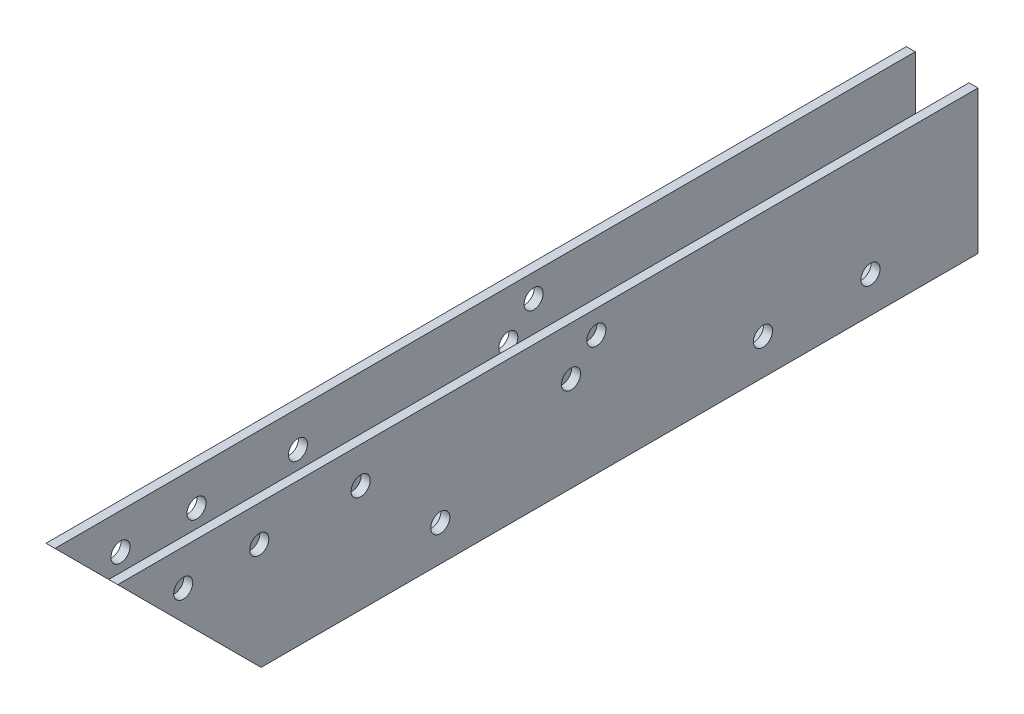
SolidWorks part; units mm, degrees
ref_plane "Front" through (0, 0, 0) normal (0, 0, 1) x (1, 0, 0)
ref_plane "Top" through (0, 0, 0) normal (0, 1, 0) x (1, 0, 0)
ref_plane "Right" through (0, 0, 0) normal (1, 0, 0) x (0, 0, -1)
sketch "Sketch1" plane through (0, 0, 0) normal (0, 0, 1) x (1, 0, 0)
  line L0 (0, -25.4) -> (0, 25.4) construction
  line L1 (-12.7, 0) -> (12.7, 0) construction
  line L2 (9.525, 25.4) -> (-9.525, 25.4) construction
  line L3 (-12.7, -25.4) -> (12.7, -25.4)
  line L4 (-12.7, -25.4) -> (-12.7, 25.4)
  line L5 (-12.7, 25.4) -> (12.7, 25.4)
  line L6 (12.7, -25.4) -> (12.7, 25.4)
  line L7 (-12.7, -25.4) -> (12.7, 25.4) construction
  line L8 (-12.7, 25.4) -> (12.7, -25.4) construction
  point P3 (0, 0)
  point P4 (0, 0)
  point P8 (0, 0)
  point P13 (12.7, 20.32)
  point P17 (0, 25.4)
  dimension "Outside Width" = 25.4
  dimension "Outside Height" = 50.8
  dimension "Inside Height" = 5.08
  dimension "Wall Thickness" = 3.175
sketch "Sketch2" plane through (0, 0, 0) normal (1, 0, 0) x (0, 0, -1)
  line L0 (-1219.2, 0) -> (1219.2, 0) construction
  dimension "Length" = 2438.4
sketch "Sketch3" plane through (0, 0, 0) normal (0, 0, 1) x (1, 0, 0)
  line L0 (-12.7, 25.4) -> (-12.7, -25.4)
  line L1 (-12.7, -25.4) -> (12.7, -25.4)
  line L2 (12.7, -25.4) -> (12.7, 25.4)
  line L3 (12.7, 25.4) -> (9.525, 25.4)
  line L4 (9.525, 25.4) -> (9.525, -22.225)
  line L5 (9.525, -22.225) -> (-9.525, -22.225)
  line L6 (-9.525, -22.225) -> (-9.525, 25.4)
  line L7 (-9.525, 25.4) -> (-12.7, 25.4)
  line L8 (-9.525, -22.225) -> (-9.525, -25.4) construction
  dimension "D1" = 50.8
  dimension "D2" = 25.4
  dimension "D3" = 3.175
extrude "Boss-Extrude2" add sketch "Sketch3" along normal mid plane 304.8
sketch "Reference Sketch1" plane through (0, 0, 0) normal (1, 0, 0) x (0, 0, -1)
  line L0 (-1219.2, 0) -> (1219.2, 0) construction
  point P0 (-1155.7, 0)
  point P1 (1155.7, 0)
  dimension "D1" = 63.5
  dimension "D2" = 63.5
sketch "Sketch4" plane through (12.7, 0, 0) normal (1, 0, 0) x (0, 0, -1)
  line L0 (-152.4, 25.4) -> (-101.6, -25.4)
  line L1 (-152.4, -25.4) -> (152.4, -25.4) construction
  line L2 (-101.6, -25.4) -> (-152.4, -25.4)
  line L3 (-152.4, -25.4) -> (-152.4, 25.4)
  dimension "D1" = 45
extrude "Cut-Extrude1" cut sketch "Sketch4" against normal through all
sketch "Sketch5" plane through (-12.7, 0, 0) normal (-1, 0, 0) x (0, 0, 1)
  circle A0 centre (-8.2099, 8.2099) radius 3.3782 construction
  circle A1 centre (-17.1901, 17.1901) radius 3.3782 construction
  circle A2 centre (-8.2099, 8.2099) radius 3.3782
  circle A3 centre (-17.1901, 17.1901) radius 3.3782
extrude "Cut-Extrude2" cut sketch "Sketch5" against normal through all
sketch "Sketch10" plane through (-12.7, 0, 0) normal (-1, 0, 0) x (0, 0, 1)
  circle A0 centre (66.3172, 12.7) radius 3.3782 construction
  circle A1 centre (66.3172, 12.7) radius 3.3782
  circle A2 centre (129.179, 12.7) radius 3.3782 construction
  circle A3 centre (102.2382, 12.7) radius 3.3782 construction
  circle A4 centre (129.179, 12.7) radius 3.3782
  circle A5 centre (102.2382, 12.7) radius 3.3782
extrude "Cut-Extrude3" cut sketch "Sketch10" against normal up to surface (25.4 mm away) up to face at (12.7, 4.8317, -8.2099)
hole_wizard "1/4 Clearance Hole1" positions "Sketch11" profile "Sketch12" hole size "1/4" standard "ANSI Inch"
sketch "Sketch11" plane through (-12.7, 0, 0) normal (-1, 0, 0) x (0, 0, 1)
  line L0 (-152.4, -12.7) -> (114.3, -12.7)
  line L1 (-152.4, 25.4) -> (-152.4, -25.4) construction
  line L2 (101.6, -25.4) -> (152.4, 25.4) construction
  line L4 (101.6, -25.4) -> (-152.4, -25.4) construction
  point P13 (-114.3, -12.7)
  point P15 (-76.2, -12.7)
  point P17 (38.1, -12.7)
  dimension "D1" = 12.7
  dimension "D2" = 38.1
  dimension "D3" = 38.1
  dimension "D4" = 114.3
sketch "Sketch12" plane through (-12.7, -12.7, 38.1) normal (0, 1, 0) x (0, 0, 1)
  line L0 (0, 0) -> (0, 27.4298)
  line L1 (0, 27.4298) -> (3.3782, 25.4)
  line L2 (3.3782, 25.4) -> (3.3782, 0)
  line L5 (3.3782, 0) -> (0, 0)
  line L10 (0, 27.4298) -> (-3.3782, 25.4) construction
  line L11 (0, -6.35) -> (0, 107.95) construction
  dimension "Hole Dia." = 6.7564
  dimension "Hole Depth" = 25.4
  dimension "Drill Angle" = 118
equation "\"D1@Sketch3\" = \"Outside Height@Sketch1\""
equation "\"D2@Sketch3\" = \"Outside Width@Sketch1\""
equation "\"D3@Sketch3\" = \"Wall Thickness@Sketch1\""
equation "\"D1@Reference Sketch1\" = \"Outside Height@Sketch1\" * 1.25"
equation "\"D2@Reference Sketch1\" = \"D1@Reference Sketch1\""
equation "\"D1@Boss-Extrude2\"=12in"
